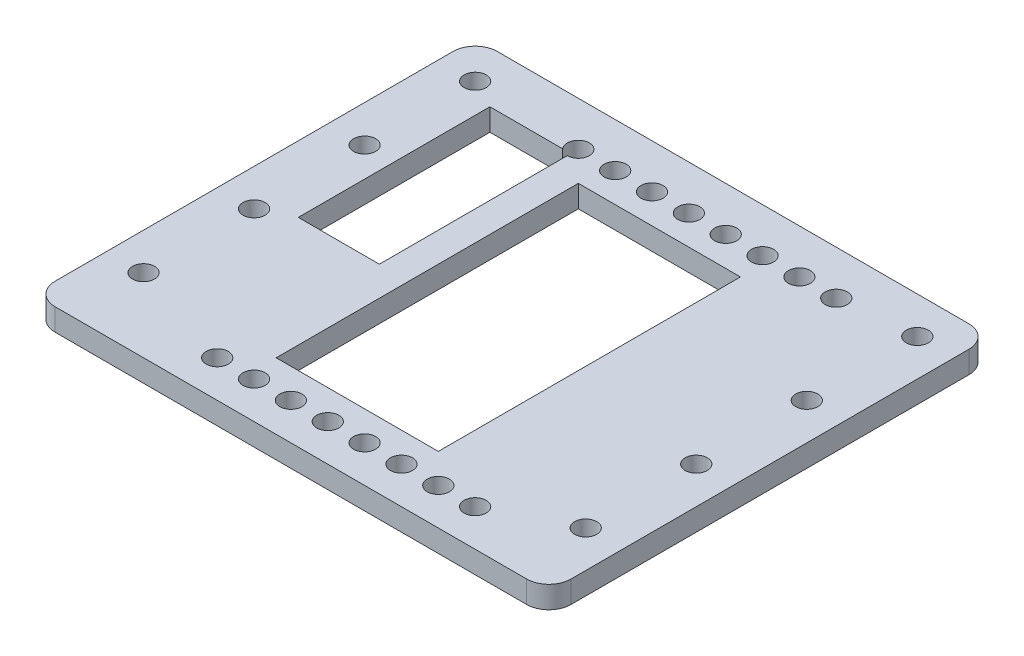
SolidWorks part; units mm, degrees
ref_plane "Front Plane" through (0, 0, 0) normal (0, 0, 1) x (1, 0, 0)
ref_plane "Top Plane" through (0, 0, 0) normal (0, 1, 0) x (1, 0, 0)
ref_plane "Right Plane" through (0, 0, 0) normal (1, 0, 0) x (0, 0, -1)
sketch "Sketch1" plane through (0, 0, 0) normal (0, 1, 0) x (1, 0, 0)
  line L1 (-35, 30) -> (35, 30)
  line L2 (-35, 30) -> (-35, -30)
  line L3 (-35, -30) -> (35, -30)
  line L4 (35, 30) -> (35, -30)
  dimension "D1" = 60
  dimension "D2" = 70
  dimension "D3" = 35
  dimension "D4" = 30
extrude "Acrylic Board" add sketch "Sketch1" along normal blind 3
sketch "Sketch2" plane through (0, 3, 0) normal (0, 1, 0) x (1, 0, 0)
  line L0 (0, 0) -> (0, 30) construction
  line L1 (35, 30) -> (-35, 30) construction
  line L2 (-35, 30) -> (-35, -30) construction
  circle A0 centre (-30, 25) radius 1.5
  circle A1 centre (30, 25) radius 1.5
  circle A2 centre (30, 10) radius 1.5
  circle A3 centre (30, -5) radius 1.5
  circle A4 centre (30, -20) radius 1.5
  circle A5 centre (-30, 10) radius 1.5
  circle A6 centre (-30, -5) radius 1.5
  circle A7 centre (-30, -20) radius 1.5
  dimension "D1" = 3
  dimension "D2" = 5
  dimension "D3" = 5
  dimension "D4" = 2
  dimension "D5" = 4
extrude "To Chassis" cut sketch "Sketch2" against normal blind 3
sketch "Sketch3" plane through (0, 3, 0) normal (0, 1, 0) x (1, 0, 0)
  line L0 (35, 30) -> (-35, 30) construction
  circle A0 centre (0, 24) radius 1.5
  circle A1 centre (5, 24) radius 1.5
  circle A2 centre (10, 24) radius 1.5
  circle A3 centre (15, 24) radius 1.5
  circle A4 centre (20, 24) radius 1.5
  circle A5 centre (5, -25) radius 1.5
  circle A6 centre (10, -25) radius 1.5
  circle A7 centre (15, -25) radius 1.5
  circle A8 centre (20, -25) radius 1.5
  circle A9 centre (0, -25) radius 1.5
  circle A10 centre (-5, 24) radius 1.5
  circle A11 centre (-10, 24) radius 1.5
  circle A12 centre (-15, 24) radius 1.5
  circle A13 centre (-5, -25) radius 1.5
  circle A14 centre (-10, -25) radius 1.5
  circle A15 centre (-15, -25) radius 1.5
  circle A16 centre (0, -25) radius 1.5
  dimension "D1" = 3
  dimension "D2" = 6
  dimension "D3" = 5
  dimension "D4" = 2
  dimension "D5" = 4
  dimension "D6" = 2
extrude "Servo Screw" cut sketch "Sketch3" against normal blind 3 contours A8 | A7 | A5 | A6 | A13 | A14 | A15 | A12 | A11 | A0 | A1 | A2 | A3 | A4 | A9 | A10
sketch "Sketch4" plane through (0, 3, 0) normal (0, 1, 0) x (1, 0, 0)
  line L0 (35, -30) -> (35, 30) construction
  line L1 (-11, 20) -> (11, 20)
  line L2 (-11, 20) -> (-11, -21)
  line L3 (-11, -21) -> (11, -21)
  line L4 (11, 20) -> (11, -21)
  line L5 (35, 30) -> (-35, 30) construction
  line L7 (-15, 23) -> (-26, 23)
  line L8 (-15, 23) -> (-15, -3)
  line L9 (-15, -3) -> (-26, -3)
  line L10 (-26, 23) -> (-26, -3)
  dimension "D1" = 22
  dimension "D2" = 41
  dimension "D3" = 24
  dimension "D4" = 10
  dimension "D5" = 11
  dimension "D6" = 26
  dimension "D7" = 7
  dimension "D8" = 4
extrude "Servo" cut sketch "Sketch4" against normal blind 3
fillet "Fillet1" radius 3 4 edges at (35, 1.5, -30) (35, 1.5, 30) (-35, 1.5, 30) (-35, 1.5, -30)
